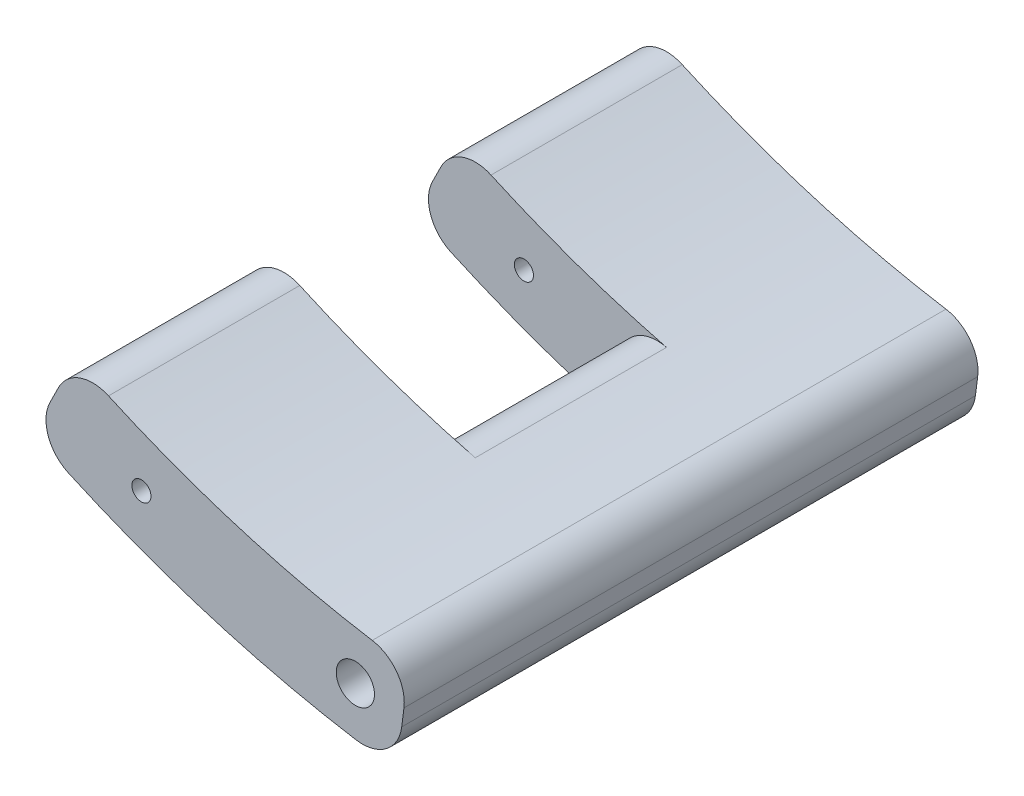
SolidWorks part; units mm, degrees
ref_plane "Front Plane" through (0, 0, 0) normal (0, 0, 1) x (1, 0, 0)
ref_plane "Top Plane" through (0, 0, 0) normal (0, 1, 0) x (1, 0, 0)
ref_plane "Right Plane" through (0, 0, 0) normal (1, 0, 0) x (0, 0, -1)
sketch "Sketch1" plane through (0, 0, 0) normal (0, 0, 1) x (1, 0, 0)
  line L0 (-24.4478, -49.2677) -> (-26.6703, -53.7466)
  line L1 (-7.0058, -54.552) -> (-7.6427, -59.5112)
  arc A0 (-24.4478, -49.2677) -> (-7.0058, -54.552) centre (0, 0) ccw
  arc A1 (-26.6703, -53.7466) -> (-7.6427, -59.5112) centre (0, 0) ccw
  dimension "D1" = 5
  dimension "D2" = 120
extrude "Boss-Extrude1" add sketch "Sketch1" along normal blind 30
ref_plane "Plane1" through (-26.6703, -53.7466, 0) normal (0.4445, 0.8958, 0) x (0, 0, -1)
sketch "Sketch2" plane through (-26.6703, -53.7466, 0) normal (0.4445, 0.8958, 0) x (0, 0, -1)
  line L0 (-30, 0) -> (0, 0) construction
  line L1 (-20, 0) -> (-10, 0)
  line L2 (-20, 0) -> (-20, -10)
  line L3 (-20, -10) -> (-10, -10)
  line L4 (-10, 0) -> (-10, -10)
  line L5 (0, -17.973) -> (0, 0) construction
  dimension "D1" = 10
  dimension "D2" = 10
  dimension "D3" = 10
extrude "Cut-Extrude2" cut sketch "Sketch2" along normal through all contours L2 L1 L4 L3
sketch "Sketch3" plane through (0, 0, 30) normal (0, 0, 1) x (1, 0, 0)
  line L0 (-24.4478, -49.2677) -> (-26.6703, -53.7466) construction
  circle A0 centre (0, 0) radius 57.5
  arc A1 (-24.4478, -49.2677) -> (-7.0058, -54.552) centre (0, 0) ccw construction
  circle A2 centre (-20.9833, -53.5346) radius 0.5
  dimension "D1" = 2.5
  dimension "D2" = 1
  dimension "D3" = 5
extrude "Cut-Extrude3" cut sketch "Sketch3" against normal blind 30 contours A0 A2
fillet "Fillet1" radius 2 6 edges at (-24.4478, -49.2677, 25) (-26.6703, -53.7466, 25) (-24.4478, -49.2677, 5) (-26.6703, -53.7466, 5) (-15.0825, -52.8916, 15) (-17.3395, -57.4399, 15)
ref_plane "Plane2" through (-7.6427, -59.5112, 0) normal (-0.1274, -0.9919, 0) x (0, 0, -1)
ref_plane "Plane3" through (-7.5153, -58.5194, 0) normal (-0.1274, -0.9919, 0) x (0, 0, -1)
sketch "Sketch4" plane through (-7.5153, -58.5194, 0) normal (-0.1274, -0.9919, 0) x (0, 0, -1)
  line L0 (-30, 0) -> (0, 0) construction
  line L1 (-30, 0) -> (0, 0)
  line L2 (-30, 0) -> (-30, -5)
  line L3 (-30, -5) -> (0, -5)
  line L4 (0, 0) -> (0, -5)
  line L5 (-30, 0) -> (-30, -17.6398) construction
  line L6 (0, -17.6398) -> (0, 0) construction
  dimension "D1" = 5
extrude "Boss-Extrude2" add sketch "Sketch4" along normal blind 10
fillet "Fillet2" radius 2 1 edges at (-12.5754, -58.6674, 15)
fillet "Fillet3" radius 2 1 edges at (-7.0058, -54.552, 15)
sketch "Sketch5" plane through (0, 0, 30) normal (0, 0, 1) x (1, 0, 0)
  line L0 (-11.2688, -68.1195) -> (-10.2206, -59.9576)
  line L1 (-8.7891, -68.4379) -> (-13.7484, -67.801) construction
  circle A0 centre (-11.014, -66.1358) radius 0.5
  dimension "D1" = 1
  dimension "D2" = 2
extrude "Cut-Extrude4" cut sketch "Sketch5" against normal through all contours L0 A0
sketch "Sketch6" plane through (0, 0, 0) normal (0.9919, -0.1274, 0) x (0, 0, -1)
  line L0 (0, -69) -> (-30, -69) construction
  line L1 (-20, -69) -> (-10, -69)
  line L2 (-20, -69) -> (-20, -63)
  line L3 (-20, -63) -> (-10, -63)
  line L4 (-10, -69) -> (-10, -63)
  line L5 (-20, -54.5993) -> (-20, -52.5791) construction
  line L6 (-10, -52.5791) -> (-10, -54.5993) construction
  dimension "D1" = 6
sketch "Sketch7" plane through (0, 0, 0) normal (0, 0, 1) x (1, 0, 0)
  line L0 (-8.0249, -62.4868) -> (-12.8062, -60.4649)
  line L1 (-8.7891, -68.4379) -> (-8.0249, -62.4868) construction
  line L2 (-8.7891, -68.4379) -> (-8.0249, -62.4868) construction
sweep "Cut-Sweep1" cut profiles "Sketch6" path "Sketch7"
sketch "Sketch8" plane through (0, 0, 0) normal (0.9919, -0.1274, 0) x (0, 0, -1)
  line L0 (-20, -69) -> (-20, -63) construction
  line L1 (-20, -66.8788) -> (-10, -66.8788)
  line L2 (-20, -66.8788) -> (-20, -69)
  line L3 (-20, -69) -> (-10, -69)
  line L4 (-10, -66.8788) -> (-10, -69)
extrude "Cut-Extrude5" cut sketch "Sketch8" against normal through all
fillet "Fillet4" radius 8 1 edges at (-12.8062, -60.4649, 15)
sketch "Sketch9" plane through (0, 0, 0) normal (0, 0, -1) x (-1, 0, 0)
  line L0 (11.014, -66.1358) -> (9.797, -56.6592)
  line L1 (13.7484, -67.801) -> (12.8062, -60.4649) construction
  arc A3 (9.797, -56.6592) -> (20.9833, -53.5346) centre (0, 0) ccw
  circle A5 centre (9.797, -56.6592) radius 1
  dimension "D1" = 2
extrude "Cut-Extrude6" cut sketch "Sketch9" against normal blind 50 and the other way through all contours L0 A5 A3 | A3 A5 L0
scale "Scale1" scale about centroid uniform scaling yes scale factor 1.9329
scale "Scale2" scale about centroid uniform scaling yes scale factor 1.5
sketch "Sketch10" plane through (0, 0, 58.4903) normal (0, 0, 1) x (1, 0, 0)
  circle A0 centre (26.9473, 109.5012) radius 173.961
  circle A1 centre (26.9473, 109.5012) radius 280.3446
extrude "Cut-Extrude7" cut sketch "Sketch10" against normal through all both and the other way through all
fillet "Fillet5" radius 6 1 edges at (4.7884, -63.0427, 15)
